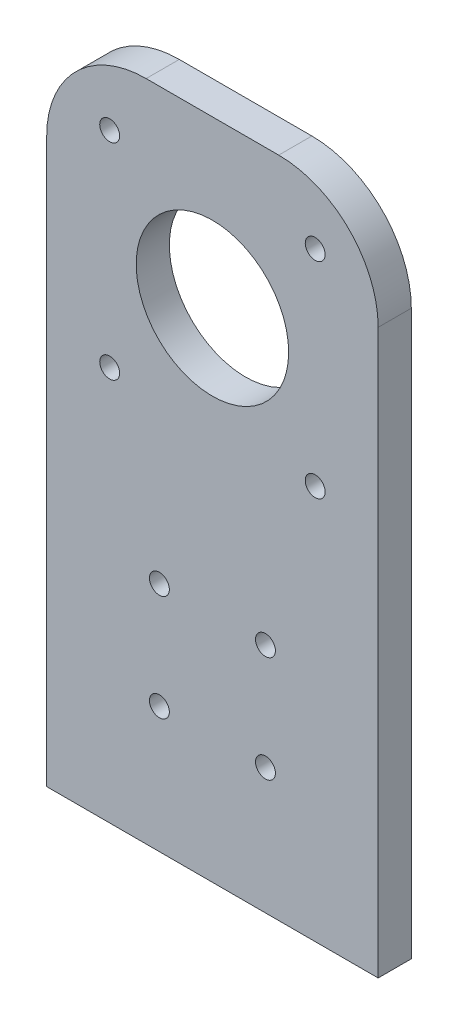
SolidWorks part; units mm, degrees
ref_plane "Front Plane" through (0, 0, 0) normal (0, 0, 1) x (1, 0, 0)
ref_plane "Top Plane" through (0, 0, 0) normal (0, 1, 0) x (1, 0, 0)
ref_plane "Right Plane" through (0, 0, 0) normal (1, 0, 0) x (0, 0, -1)
sketch "Sketch4" plane through (0, 0, 0) normal (0, 0, 1) x (1, 0, 0)
  line L0 (-10.0874, 107.0888) -> (9.9126, 107.0888)
  line L1 (-0.0874, 23.0888) -> (-0.0874, 107.0888) construction
  line L3 (-25.0874, 92.0888) -> (-25.0874, 7.0888)
  line L4 (-25.0874, 7.0888) -> (24.9126, 7.0888)
  line L5 (24.9126, 7.0888) -> (24.9126, 92.0888)
  circle A0 centre (-0.0874, 82.0888) radius 11.5
  circle A1 centre (15.4126, 66.5888) radius 1.5
  circle A2 centre (-15.5874, 66.5888) radius 1.5
  circle A3 centre (15.4126, 97.5888) radius 1.5
  circle A4 centre (-15.5874, 97.5888) radius 1.5
  circle A5 centre (-8.0874, 42.0888) radius 1.5
  circle A6 centre (7.9126, 42.0888) radius 1.5
  arc A7 (9.9126, 107.0888) -> (24.9126, 92.0888) centre (9.9126, 92.0888) cw
  arc A8 (-25.0874, 92.0888) -> (-10.0874, 107.0888) centre (-10.0874, 92.0888) cw
  point P23 (24.9126, 107.0888)
  dimension "D1" = 23
  dimension "D2" = 3
  dimension "D6" = 15
  dimension "D7" = 3
  dimension "D4" = 15.5
  dimension "D5" = 8
  dimension "D8" = 35
  dimension "D9" = 17
  dimension "D10" = 100
extrude "Boss-Extrude1" add sketch "Sketch4" along normal blind 5
sketch "Sketch5" plane through (0, 0, 0) normal (0, 0, -1) x (-1, 0, 0)
  circle A0 centre (8.0874, 26.0888) radius 1.5
  circle A1 centre (-7.9126, 26.0888) radius 1.5
extrude "Cut-Extrude1" cut sketch "Sketch5" against normal through all
